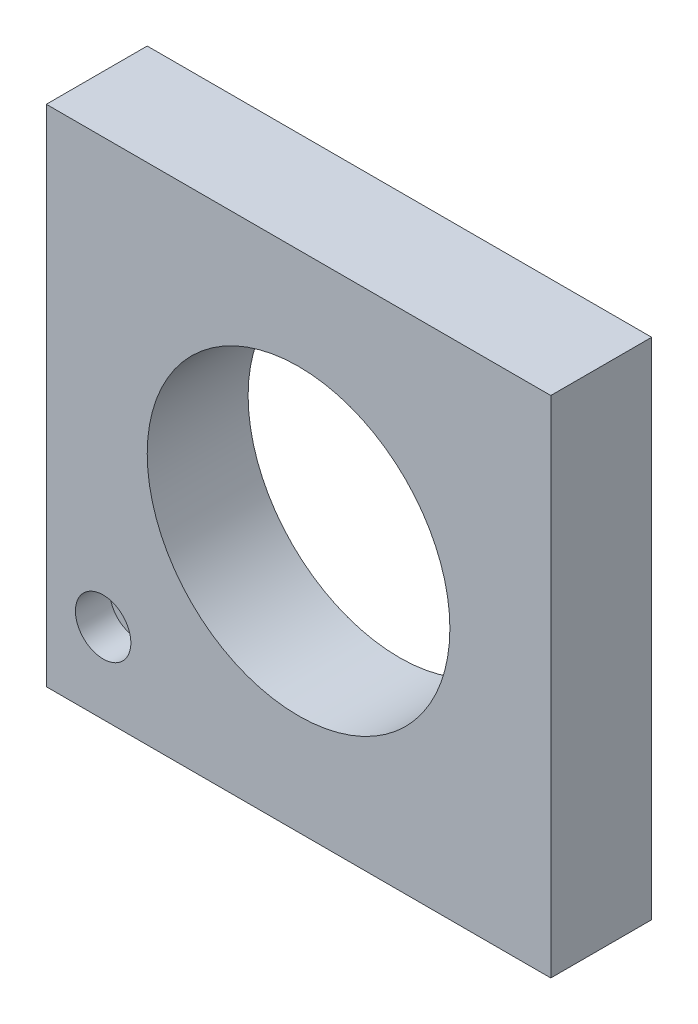
SolidWorks part; units mm, degrees
ref_plane "前视基准面" through (0, 0, 0) normal (0, 0, 1) x (1, 0, 0)
ref_plane "上视基准面" through (0, 0, 0) normal (0, 1, 0) x (1, 0, 0)
ref_plane "右视基准面" through (0, 0, 0) normal (1, 0, 0) x (0, 0, -1)
other "Configuration Table"
sketch "草图1" plane through (0, 0, 0) normal (0, 0, 1) x (1, 0, 0)
  line L1 (-50, -50) -> (50, -50)
  line L2 (-50, -50) -> (-50, 50)
  line L3 (-50, 50) -> (50, 50)
  line L4 (50, -50) -> (50, 50)
  line L5 (-50, -50) -> (50, 50) construction
  line L6 (-50, 50) -> (50, -50) construction
  point P0 (0, 0)
  dimension "D1" = 100
  dimension "D2" = 100
extrude "凸台-拉伸1" add sketch "草图1" along normal blind 20
sketch "草图2" plane through (0, 0, 20) normal (0, 0, 1) x (1, 0, 0)
  circle A0 centre (0, 0) radius 30
  point P3 (0, 0)
  dimension "D1" = 60
extrude "切除-拉伸1" cut sketch "草图2" against normal up to surface (20 mm away) contours A0 up to face at (0, 0, 0)
hole_wizard "M6 六角圆柱头螺钉的柱形沉头孔1" positions "3D草图1" profile "草图3" counterbore size "M6" standard "GB" end condition through all
sketch3d "3D草图1"
  point P0 (-38.7369, -34.1032, 20)
  point P11 (-38.7369, -34.1032, 20)
  point P13 (-38.7369, -34.1032, 20)
sketch "草图3" plane through (-38.7369, -34.1032, 20) normal (1, 0, 0) x (0, -1, 0)
  line L0 (0, 0) -> (0, 20)
  line L1 (0, 20) -> (3.3, 20)
  line L2 (3.3, 6.815) -> (3.3, 20)
  line L3 (3.3, 6.815) -> (3.325, 6.8)
  line L4 (3.325, 6.8) -> (5.5, 6.8)
  line L5 (5.5, 6.8) -> (5.5, 0)
  line L7 (0, 0) -> (5.5, 0)
  line L9 (-3.3, 6.815) -> (-3.325, 6.8) construction
  line L11 (0, -6.35) -> (0, 107.95) construction
  dimension "通孔孔直径" = 6.6
  dimension "通孔孔深度" = 20
  dimension "柱形沉头孔直径" = 11
  dimension "柱形沉头孔深度" = 6.8
  dimension "中间锥形沉头孔直径" = 6.65
  dimension "中间锥形沉头孔角度" = 118
